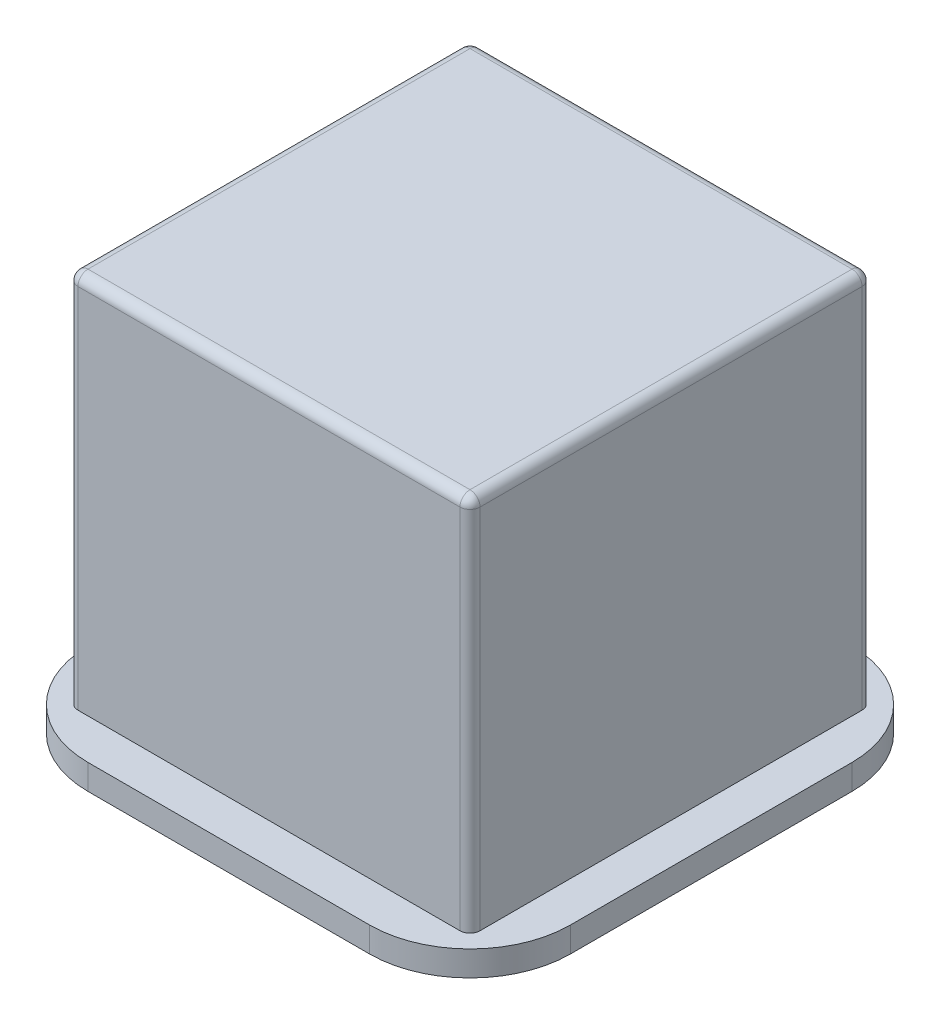
SolidWorks part; units mm, degrees
ref_plane "Front Plane" through (0, 0, 0) normal (0, 0, 1) x (1, 0, 0)
ref_plane "Top Plane" through (0, 0, 0) normal (0, 1, 0) x (1, 0, 0)
ref_plane "Right Plane" through (0, 0, 0) normal (1, 0, 0) x (0, 0, -1)
sketch "Sketch1" plane through (0, 0, 0) normal (0, 1, 0) x (1, 0, 0)
  line L1 (0, 0) -> (200, 0)
  line L2 (0, 0) -> (0, 200)
  line L3 (0, 200) -> (200, 200)
  line L4 (200, 0) -> (200, 200)
  dimension "D1" = 200
  dimension "D2" = 200
extrude "Boss-Extrude1" add sketch "Sketch1" along normal blind 200
sketch "Sketch3" plane through (0, 0, 0) normal (0, 0, 1) x (1, 0, 0)
  line L0 (200, 200) -> (200, 0) construction
  line L1 (0, 0) -> (200, 0)
  line L2 (0, 0) -> (0, 12.5)
  line L3 (0, 12.5) -> (200, 12.5)
  line L4 (200, 0) -> (200, 12.5)
  dimension "D1" = 12.5
extrude "Boss-Extrude2" add sketch "Sketch3" along normal blind 20
sketch "Sketch4" plane through (200, 0, 0) normal (1, 0, 0) x (0, 0, -1)
  line L1 (-20, 12.5) -> (200, 12.5)
  line L2 (-20, 12.5) -> (-20, 0)
  line L3 (-20, 0) -> (200, 0)
  line L4 (200, 12.5) -> (200, 0)
extrude "Boss-Extrude3" add sketch "Sketch4" along normal blind 20
sketch "Sketch5" plane through (0, 0, -200) normal (0, 0, -1) x (-1, 0, 0)
  line L1 (-220, 12.5) -> (0, 12.5)
  line L2 (-220, 12.5) -> (-220, 0)
  line L3 (-220, 0) -> (0, 0)
  line L4 (0, 12.5) -> (0, 0)
extrude "Boss-Extrude4" add sketch "Sketch5" along normal blind 20
sketch "Sketch6" plane through (0, 0, 0) normal (-1, 0, 0) x (0, 0, 1)
  line L1 (-220, 12.5) -> (20, 12.5)
  line L2 (-220, 12.5) -> (-220, 0)
  line L3 (-220, 0) -> (20, 0)
  line L4 (20, 12.5) -> (20, 0)
extrude "Boss-Extrude5" add sketch "Sketch6" along normal blind 20
fillet "Fillet1" radius 50 4 edges at (-20, 6.25, 20) (220, 6.25, 20) (220, 6.25, -220) (-20, 6.25, -220)
fillet "Fillet2" radius 5 8 edges at (200, 106.25, -200) (200, 106.25, 0) (100, 200, -200) (200, 200, -100) (0, 106.25, -200) (0, 200, -100) (100, 200, 0) (0, 106.25, 0)
